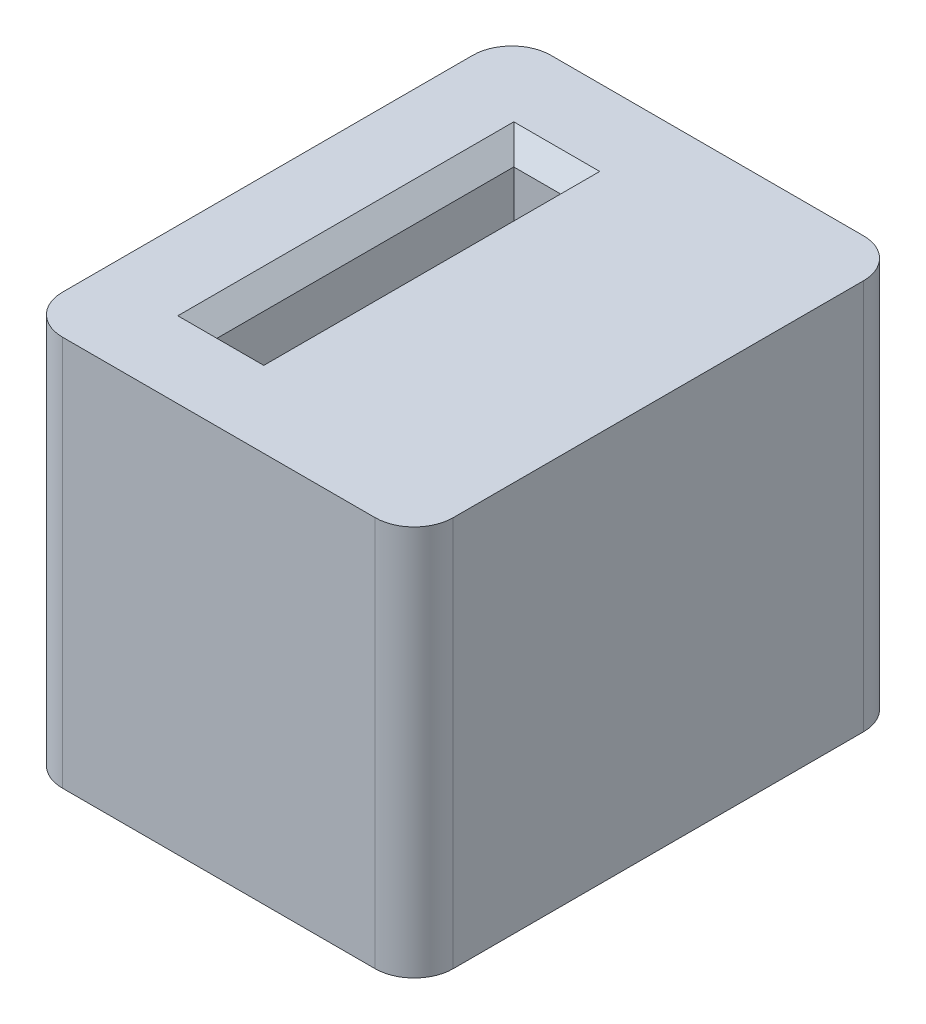
SolidWorks part; units mm, degrees
ref_plane "Front Plane" through (0, 0, 0) normal (0, 0, 1) x (1, 0, 0)
ref_plane "Top Plane" through (0, 0, 0) normal (0, 1, 0) x (1, 0, 0)
ref_plane "Right Plane" through (0, 0, 0) normal (1, 0, 0) x (0, 0, -1)
sketch "Sketch1" plane through (0, 0, 0) normal (0, 1, 0) x (1, 0, 0)
  line L1 (-12.7, 15.875) -> (12.7, 15.875)
  line L2 (-12.7, 15.875) -> (-12.7, -15.875)
  line L3 (-12.7, -15.875) -> (12.7, -15.875)
  line L4 (12.7, 15.875) -> (12.7, -15.875)
  line L5 (-12.7, 15.875) -> (12.7, -15.875) construction
  line L6 (-12.7, -15.875) -> (12.7, 15.875) construction
  point P0 (0, 0)
  dimension "D1" = 25.4
  dimension "D2" = 31.75
extrude "Boss-Extrude1" add sketch "Sketch1" along normal blind 25.4
sketch "Sketch2" plane through (0, 25.4, 0) normal (0, 1, 0) x (1, 0, 0)
  line L0 (-12.7, 15.875) -> (-12.7, -15.875) construction
  line L1 (-6.35, 9.652) -> (-3.302, 9.652)
  line L2 (-6.35, 9.652) -> (-6.35, -9.652)
  line L3 (-6.35, -9.652) -> (-3.302, -9.652)
  line L4 (-3.302, 9.652) -> (-3.302, -9.652)
  line L5 (-6.35, 9.652) -> (-3.302, -9.652) construction
  line L6 (-6.35, -9.652) -> (-3.302, 9.652) construction
  point P0 (-4.826, 0)
  dimension "D3" = 19.304
  dimension "D1" = 6.35
  dimension "D2" = 3.048
extrude "Cut-Extrude1" cut sketch "Sketch2" against normal through all
fillet "Fillet1" radius 2.54 4 edges at (12.7, 12.7, -15.875) (-12.7, 12.7, 15.875) (12.7, 12.7, 15.875) (-12.7, 12.7, -15.875)
chamfer "Chamfer1" distance 1.27 angle 45 8 edges at (-4.826, 0, 9.652) (-3.302, 0, 0) (-4.826, 0, -9.652) (-6.35, 0, 0) (-4.826, 25.4, 9.652) (-3.302, 25.4, 0) (-4.826, 25.4, -9.652) (-6.35, 25.4, 0)
